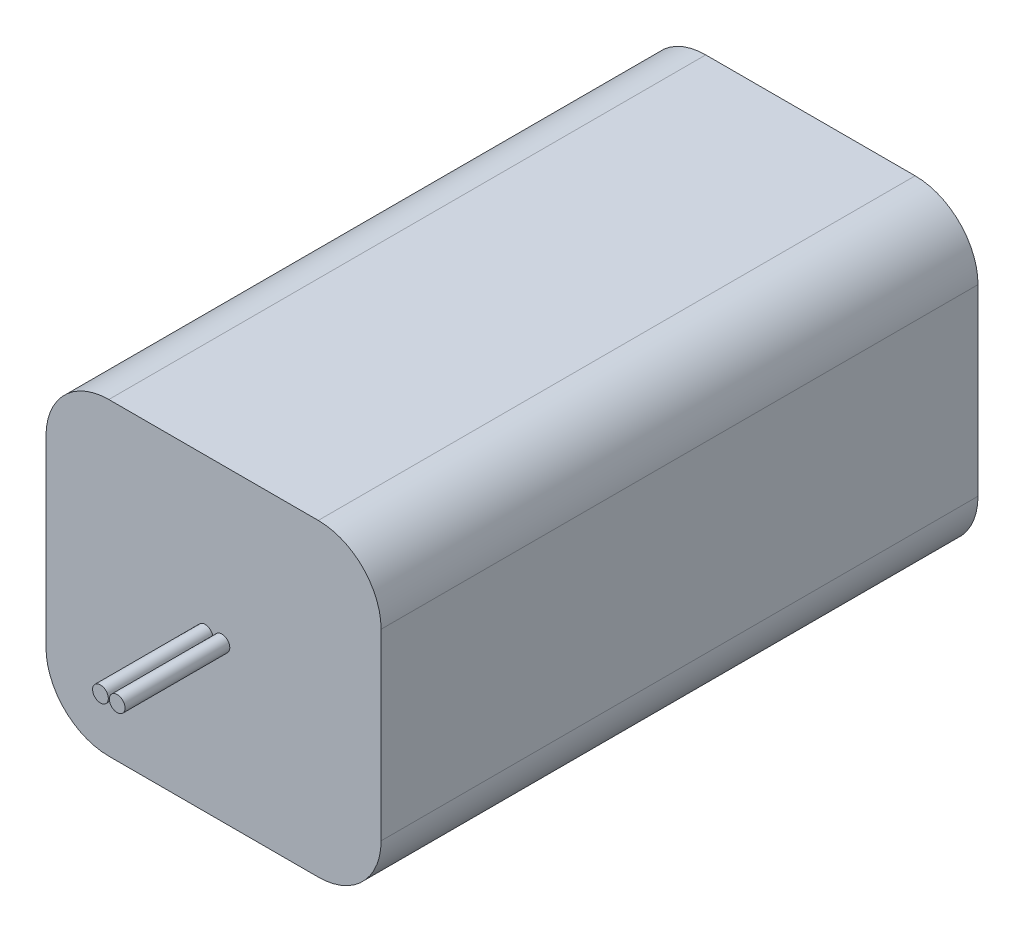
SolidWorks part; units mm, degrees
material "CA"
ref_plane "Plan de face" through (0, 0, 0) normal (0, 0, 1) x (1, 0, 0)
ref_plane "Plan de dessus" through (0, 0, 0) normal (0, 1, 0) x (1, 0, 0)
ref_plane "Plan de droite" through (0, 0, 0) normal (1, 0, 0) x (0, 0, -1)
sketch "Esquisse1" plane through (0, 0, 0) normal (0, 0, 1) x (1, 0, 0)
  line L0 (0, 14.75) -> (0, 0) construction
  line L1 (-16, 14.75) -> (16, 14.75)
  line L2 (-16, 14.75) -> (-16, -14.75)
  line L3 (-16, -14.75) -> (16, -14.75)
  line L4 (16, 14.75) -> (16, -14.75)
  line L5 (0, 0) -> (-16, 0) construction
  dimension "D1" = 32
  dimension "D2" = 29.5
extrude "Boss.-Extru.1" add sketch "Esquisse1" along normal mid plane 57
fillet "Congé1" radius 6 4 edges at (-16, -14.75, 0) (16, -14.75, 0) (16, 14.75, 0) (-16, 14.75, 0)
sketch "Esquisse2" plane through (0, 0, 28.5) normal (0, 0, 1) x (1, 0, 0)
  line L0 (-0.8, 0) -> (0.8, 0) construction
  circle A0 centre (-0.8, 0) radius 0.75
  circle A1 centre (0.8, 0) radius 0.75
  dimension "D1" = 0.1
  dimension "D2" = 1.5
extrude "Boss.-Extru.2" add sketch "Esquisse2" along normal blind 10 separate body
